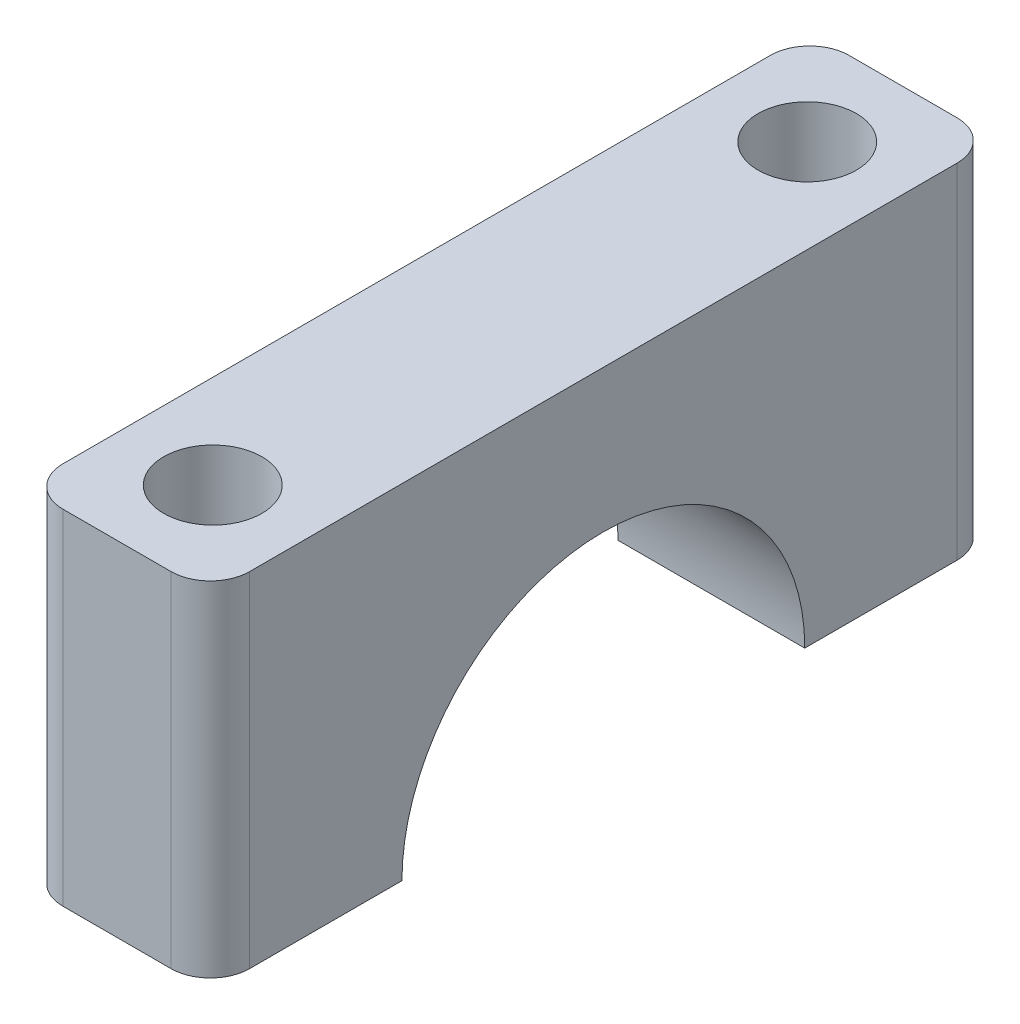
SolidWorks part; units mm, degrees
ref_plane "Front Plane" through (0, 0, 0) normal (0, 0, 1) x (1, 0, 0)
ref_plane "Top Plane" through (0, 0, 0) normal (0, 1, 0) x (1, 0, 0)
ref_plane "Right Plane" through (0, 0, 0) normal (1, 0, 0) x (0, 0, -1)
sketch "Sketch1" plane through (0, 0, 0) normal (0, 1, 0) x (1, 0, 0)
  line L1 (-9.5, -40) -> (9.5, -40)
  line L2 (-9.5, -40) -> (-9.5, 40)
  line L3 (-9.5, 40) -> (9.5, 40)
  line L4 (9.5, -40) -> (9.5, 40)
  line L5 (0, 40) -> (0, -40) construction
  line L6 (-9.5, 0) -> (9.5, 0) construction
  point P0 (0, 0)
  dimension "D1" = 80
  dimension "D2" = 19
extrude "Boss-Extrude1" add sketch "Sketch1" along normal blind 35
sketch "Sketch2" plane through (9.5, 0, 0) normal (1, 0, 0) x (0, 0, -1)
  line L0 (-20.5, 0) -> (20.5, 0)
  circle A0 centre (0, 0) radius 20.5
  line M1 (-40, 0) -> (40, 0)
  dimension "D1" = 41
extrude "Cut-Extrude1" cut sketch "Sketch2" against normal blind 35 contours A0 M1
sketch "Sketch3" plane through (0, 0, 0) normal (0, -1, 0) x (1, 0, 0)
  line L0 (-9.5, 40) -> (9.5, 20.5) construction
  line L1 (9.5, 40) -> (-9.5, 20.5) construction
  line L2 (-9.5, -20.5) -> (9.5, -40) construction
  line L3 (9.5, -20.5) -> (-9.5, -40) construction
  circle A0 centre (0, -30.25) radius 5
  circle A1 centre (0, 30.25) radius 5
  dimension "D1" = 10
  dimension "D2" = 10
extrude "Cut-Extrude2" cut sketch "Sketch3" against normal blind 35
fillet "Fillet1" radius 4 4 edges at (9.5, 17.5, 40) (-9.5, 17.5, 40) (-9.5, 17.5, -40) (9.5, 17.5, -40)
